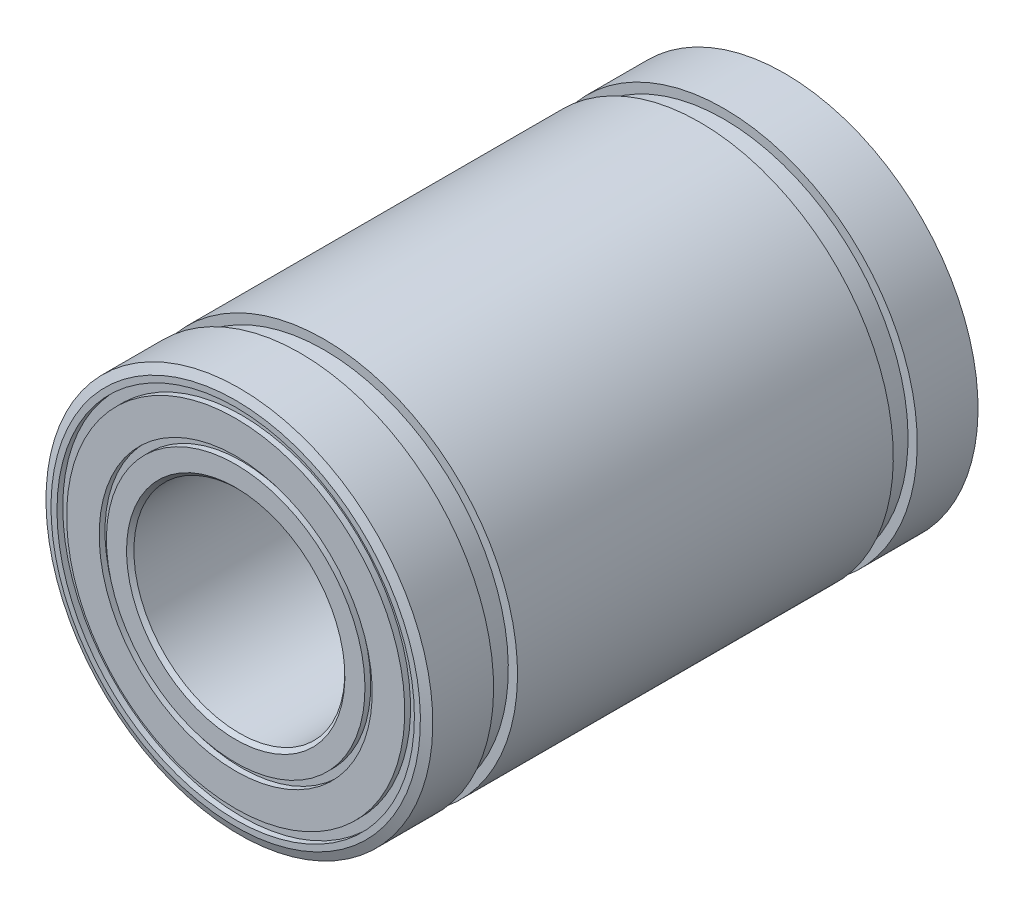
SolidWorks part; units mm, degrees
ref_plane "Front Plane" through (0, 0, 0) normal (0, 0, 1) x (1, 0, 0)
ref_plane "Top Plane" through (0, 0, 0) normal (0, 1, 0) x (1, 0, 0)
ref_plane "Right Plane" through (0, 0, 0) normal (1, 0, 0) x (0, 0, -1)
ref_plane "Plane1" through (0, 0, 0) normal (0, -1, 0) x (1, 0, 0)
sketch "Sketch1" plane through (0, 0, 0) normal (0, -1, 0) x (1, 0, 0)
  line L0 (6.4952, 15.7143) -> (6.2857, 15.5048)
  line L1 (6.2857, 15.5048) -> (6.2857, -15.5048)
  line L2 (6.2857, -15.5048) -> (6.4952, -15.7143)
  line L3 (6.4952, -15.7143) -> (7.6371, -15.7143)
  line L4 (7.6371, -15.7143) -> (7.6371, -15.3843)
  line L5 (7.6371, -15.3843) -> (8.0496, -15.3843)
  line L6 (8.0496, -15.3843) -> (8.0496, -15.7143)
  line L7 (8.0496, -15.7143) -> (9.9, -15.7143)
  line L8 (9.9, -15.7143) -> (9.9, -15.3843)
  line L9 (9.9, -15.3843) -> (10.45, -15.3843)
  line L10 (10.45, -15.3843) -> (10.45, -15.7143)
  line L11 (10.45, -15.7143) -> (10.7905, -15.7143)
  line L12 (10.7905, -15.7143) -> (11.2857, -15.5048)
  line L13 (11.2857, -15.5048) -> (11.2857, -12.0476)
  line L14 (11.2857, -12.0476) -> (10.7619, -12.0476)
  line L15 (10.7619, -12.0476) -> (10.7619, -10.6857)
  line L16 (10.7619, -10.6857) -> (11.2857, -10.6857)
  line L17 (11.2857, -10.6857) -> (11.2857, 10.6857)
  line L18 (11.2857, 10.6857) -> (10.7619, 10.6857)
  line L19 (10.7619, 10.6857) -> (10.7619, 12.0476)
  line L20 (10.7619, 12.0476) -> (11.2857, 12.0476)
  line L21 (11.2857, 12.0476) -> (11.2857, 15.5048)
  line L22 (11.2857, 15.5048) -> (10.7905, 15.7143)
  line L23 (10.7905, 15.7143) -> (10.45, 15.7143)
  line L24 (10.45, 15.7143) -> (10.45, 15.3843)
  line L25 (10.45, 15.3843) -> (9.9, 15.3843)
  line L26 (9.9, 15.3843) -> (9.9, 15.7143)
  line L27 (9.9, 15.7143) -> (8.0496, 15.7143)
  line L28 (8.0496, 15.7143) -> (8.0496, 15.3843)
  line L29 (8.0496, 15.3843) -> (7.6371, 15.3843)
  line L30 (7.6371, 15.3843) -> (7.6371, 15.7143)
  line L31 (7.6371, 15.7143) -> (6.4952, 15.7143)
  line L32 (0.2857, 15.7143) -> (0.2857, -15.7143) construction
  dimension "D1" = 11
  dimension "D2" = 6
revolve "Revolve1" add sketch "Sketch1" angle 360 about L32
